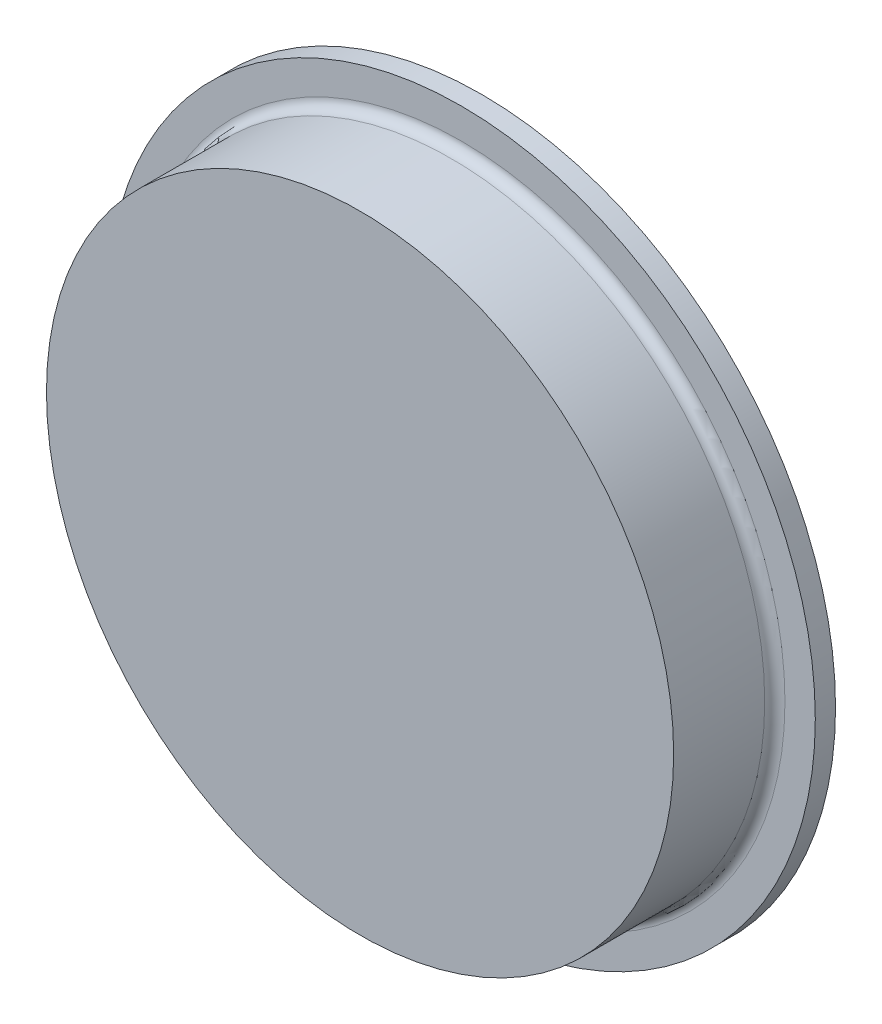
SolidWorks part; units mm, degrees
ref_plane "Front Plane" through (0, 0, 0) normal (0, 0, 1) x (1, 0, 0)
ref_plane "Top Plane" through (0, 0, 0) normal (0, 1, 0) x (1, 0, 0)
ref_plane "Right Plane" through (0, 0, 0) normal (1, 0, 0) x (0, 0, -1)
sketch "Sketch1" plane through (0, 0, 0) normal (0, 0, 1) x (1, 0, 0)
  circle A0 centre (0, 0) radius 31
  dimension "D1" = 62
extrude "Boss-Extrude1" add sketch "Sketch1" along normal mid plane 10
sketch "Sketch2" plane through (0, 0, -5) normal (0, 0, -1) x (-1, 0, 0)
  circle A0 centre (0, 0) radius 35
  dimension "D1" = 70
extrude "Boss-Extrude2" add sketch "Sketch2" along normal blind 2
sketch "Sketch3" plane through (0, 0, -7) normal (0, 0, -1) x (-1, 0, 0)
  circle A0 centre (0, 0) radius 5
  dimension "D1" = 10
extrude "Boss-Extrude3" add sketch "Sketch3" along normal blind 11
fillet "Fillet1" radius 1 2 edges at (31, 0, -5) (-5, 0, -7)
